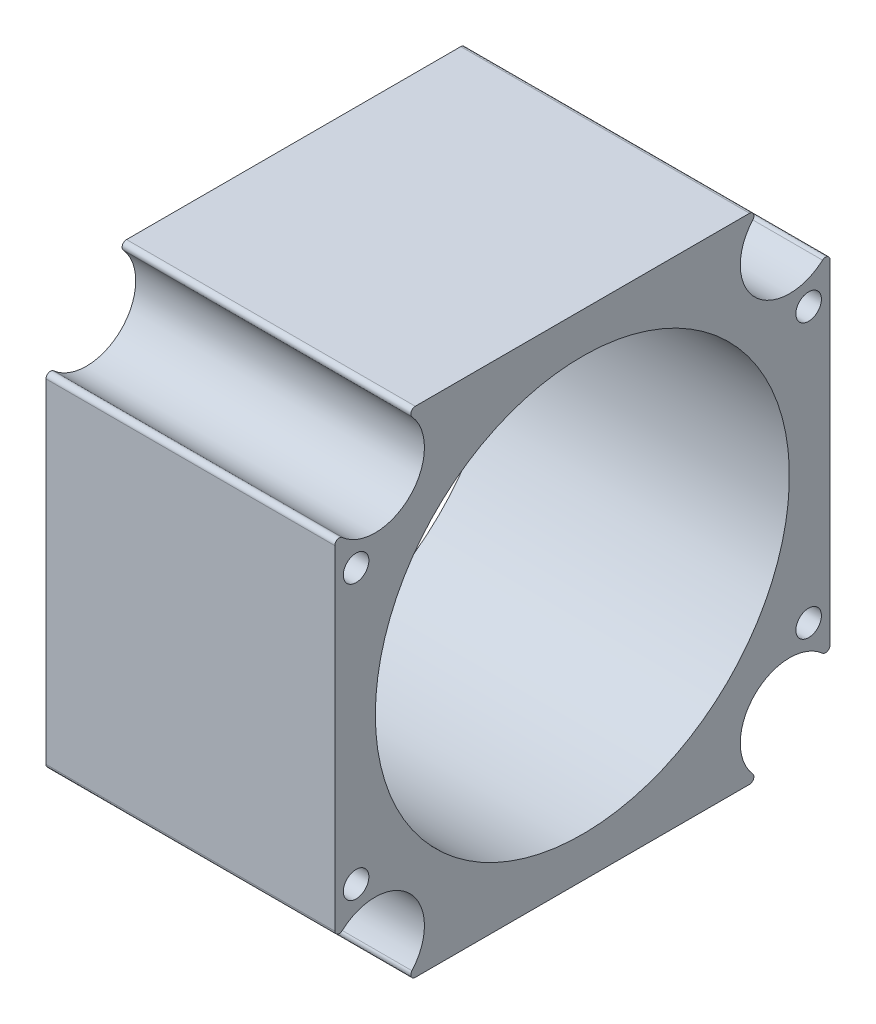
SolidWorks part; units mm, degrees
ref_plane "Front Plane" through (0, 0, 0) normal (0, 0, 1) x (1, 0, 0)
ref_plane "Top Plane" through (0, 0, 0) normal (0, 1, 0) x (1, 0, 0)
ref_plane "Right Plane" through (0, 0, 0) normal (1, 0, 0) x (0, 0, -1)
sketch "Sketch1" plane through (0, 0, 0) normal (1, 0, 0) x (0, 0, -1)
  line L0 (0, 28.067) -> (0, 0) construction
  line L1 (28.1, -18.9391) -> (28.1, 18.9391)
  line L2 (-28.1, -18.9391) -> (-28.1, 18.9391)
  line L3 (-18.9619, 28.067) -> (18.9619, 28.067)
  line L4 (-18.9619, -28.067) -> (18.9619, -28.067)
  line L5 (-28.1, -28.067) -> (28.1, 28.067) construction
  line L6 (-28.1, 28.067) -> (28.1, -28.067) construction
  line L7 (0, 0) -> (-28.1, 0) construction
  arc A0 (-27.2536, 19.318) -> (-19.3412, 27.221) centre (-23.5226, 23.495) ccw
  arc A1 (-18.9619, 28.067) -> (-19.3412, 27.221) centre (-18.9619, 27.559) ccw
  arc A2 (-28.1, 18.9391) -> (-27.2536, 19.318) centre (-27.592, 18.9391) cw
  arc A3 (28.1, 18.9391) -> (27.2536, 19.318) centre (27.592, 18.9391) ccw
  arc A4 (18.9619, 28.067) -> (19.3412, 27.221) centre (18.9619, 27.559) cw
  arc A5 (27.2536, 19.318) -> (19.3412, 27.221) centre (23.5226, 23.495) cw
  arc A6 (27.2536, -19.318) -> (19.3412, -27.221) centre (23.5226, -23.495) ccw
  arc A7 (18.9619, -28.067) -> (19.3412, -27.221) centre (18.9619, -27.559) ccw
  arc A8 (28.1, -18.9391) -> (27.2536, -19.318) centre (27.592, -18.9391) cw
  arc A9 (-28.1, -18.9391) -> (-27.2536, -19.318) centre (-27.592, -18.9391) ccw
  arc A10 (-18.9619, -28.067) -> (-19.3412, -27.221) centre (-18.9619, -27.559) cw
  arc A11 (-27.2536, -19.318) -> (-19.3412, -27.221) centre (-23.5226, -23.495) cw
  point P0 (0, 0)
  point P38 (28.1, 0)
  dimension "D3" = 11.2014
  dimension "D5" = 0.508
  dimension "D4" = 46.99
extrude "Boss-Extrude1" add sketch "Sketch1" along normal blind 32.766
sketch "Sketch2" plane through (0, 0, 0) normal (-1, 0, 0) x (0, 0, 1)
  circle A0 centre (0, 0) radius 23.495
  dimension "D1" = 46.99
extrude "Cut-Extrude1" cut sketch "Sketch2" against normal through all
hole_wizard "M3.5x0.6 Tapped Hole1" positions "Sketch3" profile "Sketch4" tap size "M3.5x0.6" standard "ANSI Metric" end condition through all
sketch "Sketch3" plane through (32.766, 0, 0) normal (1, 0, 0) x (0, 0, -1)
  point P0 (25.6794, 15.5443)
  point P2 (25.6794, -15.5443)
  point P4 (-25.6794, 15.5443)
  point P6 (-25.6794, -15.5443)
sketch "Sketch4" plane through (32.766, 15.5443, -25.6794) normal (0, 1, 0) x (0, 0, -1)
  line L0 (0, 0) -> (0, 32.766)
  line L1 (0, 32.766) -> (1.45, 32.766)
  line L2 (1.45, 32.766) -> (1.45, 0)
  line L5 (1.45, 0) -> (0, 0)
  line L11 (0, -6.35) -> (0, 107.95) construction
  dimension "Thru Tap Drill Dia." = 2.9
  dimension "Thru Tap Drill Depth" = 32.766
cosmetic thread "Hole Thread1" parameters "D2"=3.5
cosmetic thread "Hole Thread2" parameters "D2"=3.5
cosmetic thread "Hole Thread3" parameters "D2"=3.5
cosmetic thread "Hole Thread4" parameters "D2"=3.5
